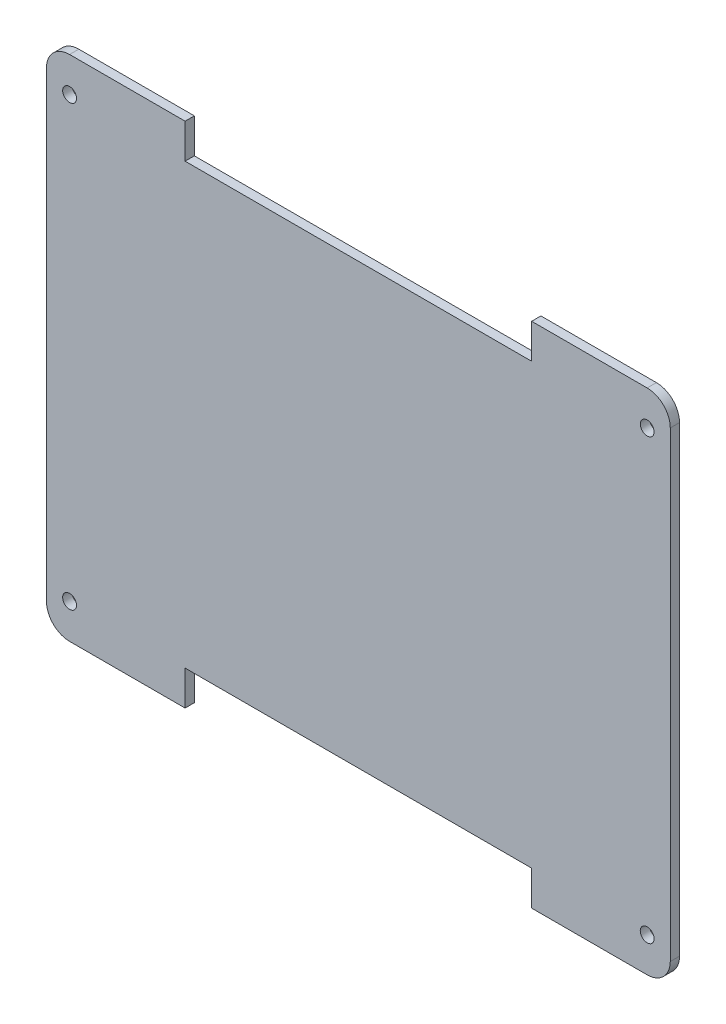
SolidWorks part; units mm, degrees
ref_plane "Front Plane" through (0, 0, 0) normal (0, 0, 1) x (1, 0, 0)
ref_plane "Top Plane" through (0, 0, 0) normal (0, 1, 0) x (1, 0, 0)
ref_plane "Right Plane" through (0, 0, 0) normal (1, 0, 0) x (0, 0, -1)
sketch "Sketch1" plane through (0, 0, 0) normal (0, 0, 1) x (1, 0, 0)
  line L0 (-135, -20.6351) -> (-135, -50)
  line L1 (-135, 50) -> (135, 50)
  line L2 (-135, 50) -> (-135, 40)
  line L3 (-135, -50) -> (135, -50)
  line L4 (135, 50) -> (135, 40)
  line L5 (-135, 50) -> (135, -50) construction
  line L6 (-135, -50) -> (135, 50) construction
  line L7 (-127, 40) -> (-94, 40)
  line L8 (0, -20) -> (0, -50) construction
  line L9 (-127, -40) -> (-94, -40)
  line L10 (-94, 40) -> (-94, -40)
  line L11 (-61, -30) -> (-35, -30)
  line L12 (-61, -30) -> (-61, 30)
  line L13 (-61, 30) -> (-35, 30)
  line L14 (-35, -30) -> (-35, -20)
  line L15 (-35, 20) -> (-35, 30)
  line L16 (-35, -20) -> (-4, -20)
  line L17 (35, 20) -> (35, 30)
  line L18 (-35, 20) -> (-4, 20)
  line L19 (135, -20.6351) -> (135, -50)
  line L20 (35, -30) -> (35, -20)
  line L21 (61, 30) -> (35, 30)
  line L22 (61, -30) -> (61, 30)
  line L23 (61, -30) -> (35, -30)
  line L24 (135, -20.6351) -> (135, 40)
  line L26 (94, -35) -> (127, -35)
  line L27 (4, 20) -> (35, 20)
  line L28 (94, -35) -> (94, 45)
  line L29 (-4, -20) -> (-4, 20)
  line L30 (4, -20) -> (35, -20)
  line L31 (4, -20) -> (4, 20)
  line L32 (94, 45) -> (127, 45)
  line L33 (-135, 40) -> (-135, -20.6351)
  line L34 (127, -35) -> (127, 45)
  line L35 (-127, 40) -> (-127, -40)
  circle A0 centre (-85, -43) radius 3
  circle A1 centre (-80, 43) radius 3
  circle A2 centre (80, 43) radius 3
  circle A3 centre (85, -43) radius 3
  point P0 (0, 0)
  point P14 (-94, 0)
  point P15 (-61, 0)
  dimension "D10" = 6
  dimension "D13" = 6
  dimension "D15" = 7
  dimension "D1" = 270
  dimension "D2" = 100
  dimension "D4" = 10
  dimension "D5" = 80
  dimension "D6" = 60
  dimension "D7" = 26
  dimension "D8" = 35
  dimension "D9" = 40
  dimension "D11" = 55
  dimension "D12" = 3
  dimension "D14" = 50
  dimension "D16" = 10
  dimension "D17" = 8
  dimension "D18" = 8
  dimension "D19" = 33
  dimension "D20" = 33
  dimension "D21" = 80
  dimension "D22" = 15
  dimension "D23" = 8
extrude "Boss-Extrude1" add sketch "Sketch1" along normal blind 14
sketch "Sketch4" plane through (0, 0, 0) normal (0, 0, -1) x (-1, 0, 0)
  line L0 (135, -50) -> (-135, -50) construction
  line L1 (-135, -50) -> (-135, 50) construction
  circle A0 centre (-131, 5) radius 2 construction
  circle A1 centre (-131, 5) radius 2 construction
  circle A2 centre (-131.5, 5) radius 2
  dimension "D1" = 4
  dimension "D2" = 55
  dimension "D3" = 3.5
extrude "Cut-Extrude2" cut sketch "Sketch4" against normal blind 10
sketch "Sketch5" plane through (0, 0, 0) normal (0, 0, -1) x (-1, 0, 0)
  circle A0 centre (-69, 5) radius 2 construction
  circle A1 centre (-69, 5) radius 2
extrude "Cut-Extrude3" cut sketch "Sketch5" against normal blind 10
ref_plane "Plane1" through (0, 0, 0) normal (-1, 0, 0) x (0, 0, 1)
mirror "Mirror1" about plane through (0, 0, 0) normal (-1, 0, 0) of "Cut-Extrude2", "Cut-Extrude3"
sketch "Sketch6" plane through (0, 0, 14) normal (0, 0, 1) x (1, 0, 0)
  line L0 (75, 110) -> (125, 110)
  line L1 (-135, 50) -> (135, 50)
  line L2 (-135, 50) -> (-135, 100)
  line L3 (-125, 110) -> (-75, 110)
  line L4 (135, 50) -> (135, 100)
  line L5 (-127, 0) -> (-94, 0) construction
  line L6 (-75, 110) -> (-75, 95)
  line L7 (-75, 95) -> (75, 95)
  line L8 (75, 110) -> (75, 95)
  line L9 (-127, 40) -> (-127, -40) construction
  line L10 (-94, -40) -> (-94, 40) construction
  line L11 (75, -110) -> (75, -95)
  line L12 (-75, -95) -> (75, -95)
  line L13 (-75, -110) -> (-75, -95)
  line L14 (135, -50) -> (135, -100)
  line L15 (-125, -110) -> (-75, -110)
  line L16 (-135, -50) -> (-135, -100)
  line L17 (-135, -50) -> (135, -50)
  line L18 (75, -110) -> (125, -110)
  circle A0 centre (125, -95) radius 3
  circle A1 centre (-125, 95) radius 3
  arc A2 (125, 110) -> (135, 100) centre (125, 100) cw
  arc A3 (-135, 100) -> (-125, 110) centre (-125, 100) cw
  circle A4 centre (125, 95) radius 3
  arc A5 (-135, -100) -> (-125, -110) centre (-125, -100) ccw
  arc A6 (125, -110) -> (135, -100) centre (125, -100) ccw
  circle A7 centre (-125, -95) radius 3
  point P12 (135, 110)
  point P15 (-135, 110)
  point P41 (-135, -110)
  point P42 (135, -110)
  dimension "D3" = 10
  dimension "D4" = 6
  dimension "D5" = 10
  dimension "D7" = 15
  dimension "D8" = 10
  dimension "D12" = 6
  dimension "D14" = 15
  dimension "D1" = 270
  dimension "D2" = 60
  dimension "D9" = 150
  dimension "D10" = 60
  dimension "D11" = 15
extrude "Boss-Extrude2" add sketch "Sketch6" against normal blind 4 separate body
combine bodies "Combine1" operation type add bodies to combine 108 105
combine bodies "Combine2" operation type add bodies to combine 107 109
sketch "Sketch7" plane through (0, 0, 14) normal (0, 0, 1) x (1, 0, 0)
  line L0 (135, -100) -> (135, 100) construction
  line L1 (75, -110) -> (125, -110) construction
  line L2 (-75, -95) -> (75, -95) construction
  line L3 (-127, 0) -> (-94, 0) construction
  line L4 (-127, 40) -> (-127, -40) construction
  line L5 (-94, -40) -> (-94, 40) construction
  circle A0 centre (11.25, -76.4952) radius 1.5
  circle A1 centre (-11.25, -76.4952) radius 1.5
  circle A2 centre (0, -57.0096) radius 1.5
  circle A3 centre (0, -70) radius 15.6
  circle A4 centre (0, 70) radius 6.85
  circle A5 centre (0, -70) radius 6.85
  circle A6 centre (0, 70) radius 15.6
  circle A7 centre (0, 57.0096) radius 1.5
  circle A8 centre (-11.25, 76.4952) radius 1.5
  circle A9 centre (11.25, 76.4952) radius 1.5
  point P19 (0, -95)
  dimension "D1" = 13.7
  dimension "D2" = 31.2
  dimension "D3" = 3
  dimension "D5" = 11.25
  dimension "D6" = 19.4856
  dimension "D7" = 22.5
  dimension "D8" = 12.9904
  dimension "D9" = 25
  dimension "D4" = 10
  dimension "D11" = 210
extrude "Cut-Extrude4" cut sketch "Sketch7" against normal blind 10 contours A4 | A8 | A7 | A5 | A2 | A9 | A1 | A0
sketch "Esquisse2" plane through (0, -50, 0) normal (0, -1, 0) x (1, 0, 0)
  line L1 (135, 0) -> (-135, 0)
  line L2 (135, 0) -> (135, 10)
  line L3 (135, 10) -> (-135, 10)
  line L4 (-135, 0) -> (-135, 10)
extrude "Enlèv. mat.-Extru.1" cut sketch "Esquisse2" against normal blind 260
sketch "Esquisse3" plane through (135, 0, 0) normal (1, 0, 0) x (0, 0, -1)
  line L0 (-14, -100) -> (-14, 100) construction
  line L1 (-14, 88.4785) -> (-10, 88.4785)
  line L2 (-14, 88.4785) -> (-14, -87.9887)
  line L3 (-14, -87.9887) -> (-10, -87.9887)
  line L4 (-10, 88.4785) -> (-10, -87.9887)
  line L5 (-10, -100) -> (-10, 100) construction
extrude "Boss.-Extru.3" add sketch "Esquisse3" against normal blind 265
